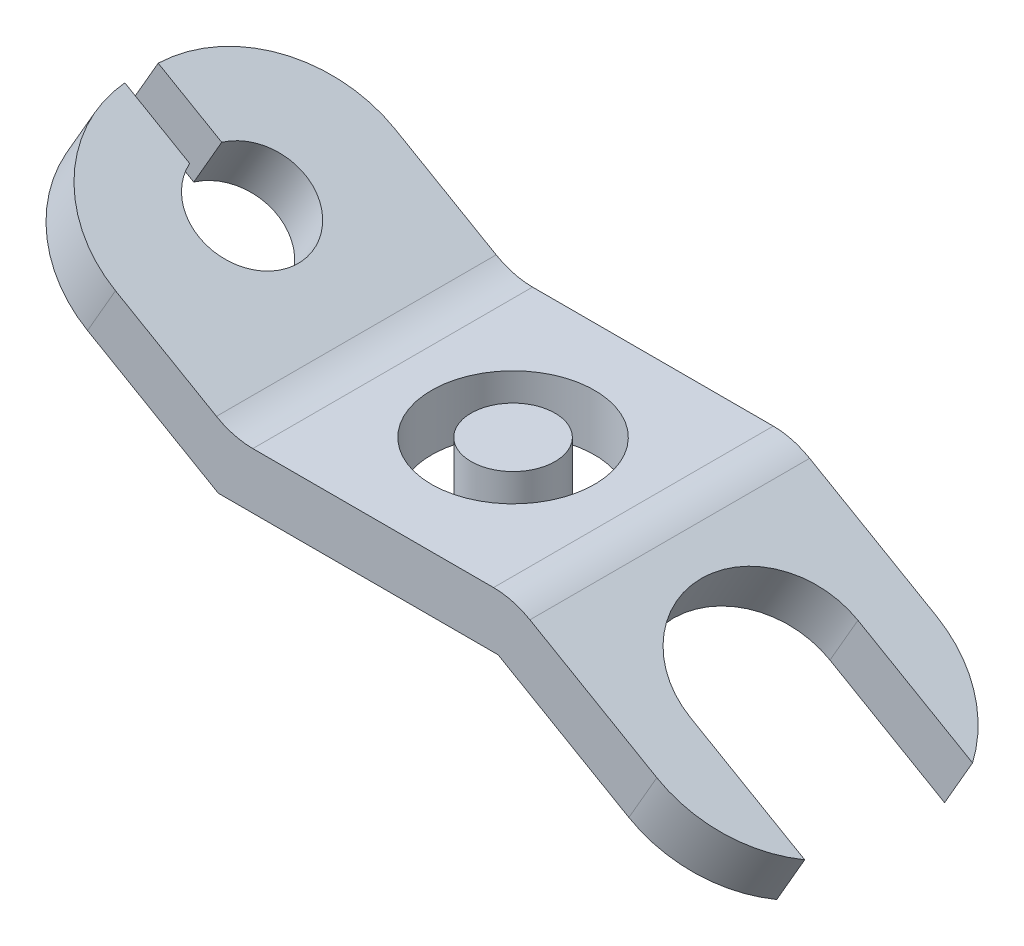
SolidWorks part; units mm, degrees
ref_plane "Front Plane" through (0, 0, 0) normal (0, 0, 1) x (1, 0, 0)
ref_plane "Top Plane" through (0, 0, 0) normal (0, 1, 0) x (1, 0, 0)
ref_plane "Right Plane" through (0, 0, 0) normal (1, 0, 0) x (0, 0, -1)
sketch "Sketch1" plane through (0, 0, 0) normal (0, 0, 1) x (1, 0, 0)
  line L0 (0, 0) -> (50, 0)
  line L1 (50, 0) -> (93.3013, -25)
  line L2 (0, 0) -> (-43.3013, 25)
  dimension "D1" = 50
  dimension "D2" = 50
  dimension "D3" = 50
  dimension "D4" = 30
  dimension "D5" = 30
extrude "Extrude-Thin1" add sketch "Sketch1" along normal blind 50 thin thin type one direction wall 10
fillet "Fillet1" radius 23 2 edges at (-40.8013, 29.3301, 0) (-40.8013, 29.3301, 50)
sketch "Sketch2" plane through (5, 8.6603, 0) normal (0.5, 0.866, 0) x (0.866, -0.5, 0)
  line L0 (-2.6795, -50) -> (-2.6795, 0) construction
  line L4 (-36.5738, -28.4557) -> (-49.9539, -28.4557)
  line L5 (-36.8761, -22.4557) -> (-49.9936, -22.4557)
  line L10 (-2.6795, 0) -> (-27, 0)
  line L11 (-50, -23) -> (-50, -27)
  line L12 (-27, -50) -> (-2.6795, -50)
  line L13 (-2.6795, -50) -> (-2.6795, 0)
  line L14 (-2.6795, 0) -> (-27, 0)
  line L15 (-50, -23) -> (-50, -27)
  line L16 (-27, -50) -> (-2.6795, -50)
  line L17 (-2.6795, -50) -> (-2.6795, 0)
  circle A0 centre (-27.6795, -25) radius 9.542
  arc A2 (-50, -27) -> (-27, -50) centre (-27, -27) ccw construction
  arc A3 (-27, 0) -> (-50, -23) centre (-27, -23) ccw construction
  arc A6 (-27, 0) -> (-50, -23) centre (-27, -23) ccw
  arc A7 (-50, -27) -> (-27, -50) centre (-27, -27) ccw
  arc A8 (-27, 0) -> (-50, -23) centre (-27, -23) ccw
  arc A9 (-50, -27) -> (-27, -50) centre (-27, -27) ccw
  point P15 (-43.4348, -22.4557)
  arc M12 (-27, 0) -> (-50, -23) centre (-27, -23) ccw
  line M13 (-50, -23) -> (-50, -27)
  arc M14 (-50, -27) -> (-27, -50) centre (-27, -27) ccw
  dimension "D1" = 25
  dimension "D2" = 6
  dimension "D3" = 0
extrude "Cut-Extrude1" cut sketch "Sketch2" against normal blind 10 contours A0 | A0 L5 L4 M12 M13 M14
fillet "Fillet2" radius 23 2 edges at (95.8013, -20.6699, 0) (95.8013, -20.6699, 50)
sketch "Sketch4" plane through (17.5, 30.3109, 0) normal (0.5, 0.866, 0) x (0.866, -0.5, 0)
  line L0 (65.6218, -25) -> (93.3013, -25) construction
  line L1 (93.3013, -27) -> (93.3013, -23) construction
  line L2 (65.6218, -10) -> (93.3013, -10)
  line L3 (65.6218, -40) -> (93.3013, -40)
  line L4 (40.6218, -50) -> (40.6218, 0) construction
  line L5 (70.3013, 0) -> (40.6218, 0) construction
  line L6 (70.3013, -50) -> (40.6218, -50) construction
  arc A0 (65.6218, -10) -> (65.6218, -40) centre (65.6218, -25) ccw
  arc A1 (93.3013, -40) -> (93.3013, -10) centre (93.3013, -25) ccw
  point P4 (79.4615, -25)
  dimension "D1" = 15
  dimension "D2" = 25
  dimension "D3" = 10
  dimension "D4" = 10
extrude "Cut-Extrude2" cut sketch "Sketch4" against normal blind 10
sketch "Sketch5" plane through (0, 10, 0) normal (0, 1, 0) x (1, 0, 0)
  line L0 (52.6795, 0) -> (2.6795, 0) construction
  line L1 (52.6795, -50) -> (52.6795, 0) construction
  circle A0 centre (27.6795, -25) radius 14.5725
  circle A1 centre (27.6795, -25) radius 7.5
  dimension "D1" = 25
  dimension "D2" = 25
extrude "Cut-Extrude3" cut sketch "Sketch5" against normal blind 10
fillet "Fillet3" radius 13 2 edges at (52.6795, 10, 25) (2.6795, 10, 25)
